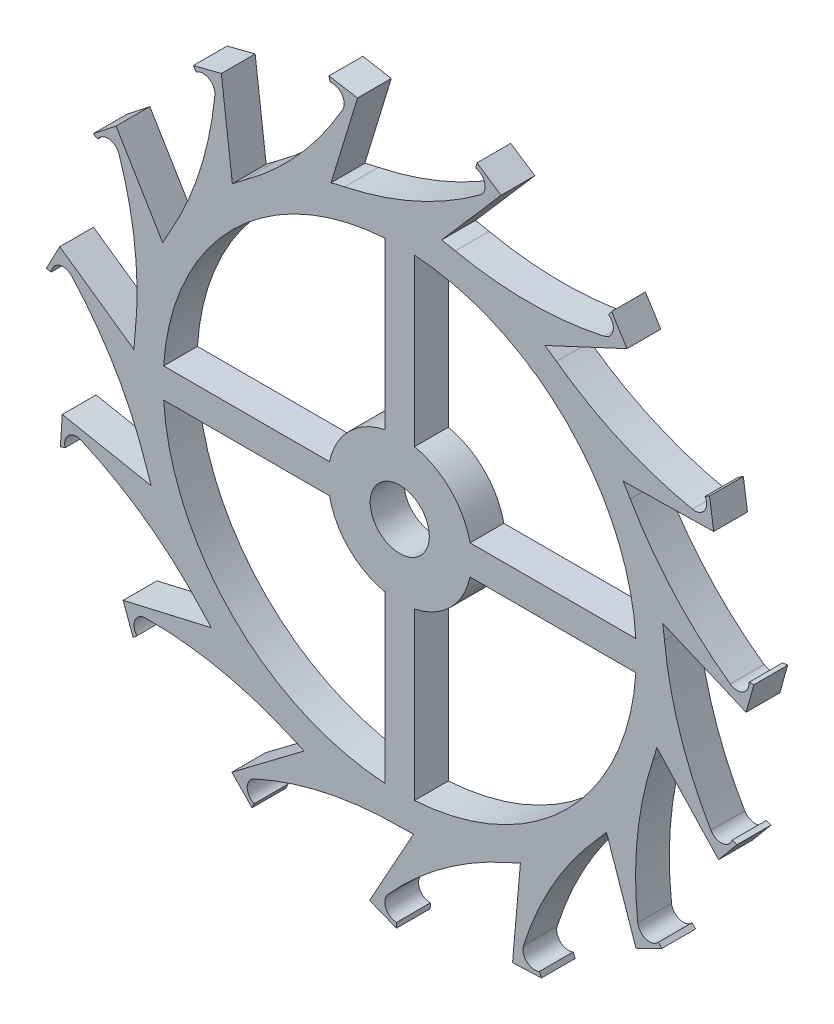
SolidWorks part; units mm, degrees
material "Brass"
ref_plane "Front Plane" through (0, 0, 0) normal (0, 0, 1) x (1, 0, 0)
ref_plane "Top Plane" through (0, 0, 0) normal (0, 1, 0) x (1, 0, 0)
ref_plane "Right Plane" through (0, 0, 0) normal (1, 0, 0) x (0, 0, -1)
sketch "Sketch1" plane through (0, 0, 0) normal (0, 0, 1) x (1, 0, 0)
  line L0 (0, -21.2809) -> (0, 20.8576) construction
  line L1 (-23.4901, 0) -> (24.9244, 0) construction
  line L2 (0, 0) -> (5.5969, 9.6942) construction
  line L3 (0, 0) -> (-5.6466, 9.7801) construction
  line L4 (2.05, 3.5507) -> (-1.6508, 5.6874) construction
  line L5 (-2.05, 3.5507) -> (1.6508, 5.6874) construction
  line L6 (0.8318, 0.175) -> (2.7945, 0.175)
  line L7 (0.8318, -0.175) -> (2.7945, -0.175)
  line L8 (-0.175, 0.8318) -> (-0.175, 2.7945)
  line L9 (0.175, 0.8318) -> (0.175, 2.7945)
  line L10 (0.175, -0.8318) -> (0.175, -2.7945)
  line L11 (-0.175, -0.8318) -> (-0.175, -2.7945)
  line L12 (-0.8318, -0.175) -> (-2.7945, -0.175)
  line L13 (-0.8318, 0.175) -> (-2.7945, 0.175)
  line L14 (0, 0) -> (6.6911, 7.6973) construction
  line L15 (0, 0) -> (-6.6911, 7.6973) construction
  line L16 (0, 4.7343) -> (6.5895, 2.1386) construction
  line L17 (2.6898, 3.0943) -> (2.2024, 3.8667)
  line L18 (0, 0) -> (2.5071, 3.384) construction
  line L19 (2.5071, 3.384) -> (2.4713, 3.3358)
  line L20 (2.6898, 3.0943) -> (1.7172, 2.6408)
  line L21 (3.6667, 2.0717) -> (3.6145, 2.0422)
  line L22 (3.7159, 1.7327) -> (3.5847, 2.6366)
  line L23 (3.7159, 1.7327) -> (2.6429, 1.714)
  line L24 (4.1923, 0.4012) -> (4.1326, 0.3955)
  line L25 (4.0994, 0.0716) -> (4.3472, 0.9506)
  line L26 (4.0994, 0.0716) -> (3.1115, 0.4909)
  line L27 (3.9931, -1.3387) -> (3.9362, -1.3196)
  line L28 (3.7741, -1.602) -> (4.3581, -0.8998)
  line L29 (3.7741, -1.602) -> (3.0422, -0.8171)
  line L30 (3.1034, -2.847) -> (3.0592, -2.8065)
  line L31 (2.7962, -2.9986) -> (3.6153, -2.5945)
  line L32 (2.7962, -2.9986) -> (2.4468, -1.9838)
  line L33 (1.6771, -3.8632) -> (1.6532, -3.8081)
  line L34 (1.3348, -3.8766) -> (2.2475, -3.8407)
  line L35 (1.3348, -3.8766) -> (1.4284, -2.8075)
  line L36 (-0.0392, -4.2113) -> (-0.0387, -4.1513)
  line L37 (-0.3573, -4.0844) -> (0.491, -4.4228)
  line L38 (-0.3573, -4.0844) -> (0.1629, -3.1458)
  line L39 (-1.7487, -3.8313) -> (-1.7238, -3.7767)
  line L40 (-1.9877, -3.5859) -> (-1.3504, -4.2401)
  line L41 (-1.9877, -3.5859) -> (-1.1306, -2.9401)
  line L42 (-3.1558, -2.7888) -> (-3.1109, -2.749)
  line L43 (-3.2744, -2.4674) -> (-2.9582, -3.3243)
  line L44 (-3.2744, -2.4674) -> (-2.2287, -2.226)
  line L45 (-4.0173, -1.2641) -> (-3.9601, -1.2461)
  line L46 (-3.9949, -0.9223) -> (-4.0546, -1.8337)
  line L47 (-3.9949, -0.9223) -> (-2.9415, -1.1271)
  line L48 (-4.1841, 0.4792) -> (-4.1245, 0.4724)
  line L49 (-4.0247, 0.7823) -> (-4.4499, -0.026)
  line L50 (-4.0247, 0.7823) -> (-3.1456, 0.1668)
  line L51 (-3.6275, 2.1396) -> (-3.5758, 2.1091)
  line L52 (-3.3585, 2.3517) -> (-4.0757, 1.7862)
  line L53 (-3.3585, 2.3517) -> (-2.8058, 1.4318)
  line L54 (-2.4436, 3.4301) -> (-2.4088, 3.3812)
  line L55 (-2.1117, 3.5144) -> (-2.9969, 3.2895)
  line L56 (-2.1117, 3.5144) -> (-1.9809, 2.4492)
  line L57 (-0.8372, 4.1274) -> (-0.8253, 4.0686)
  line L58 (-0.4997, 4.0694) -> (-0.8372, 4.1274)
  line L59 (-0.4997, 4.0694) -> (-0.8134, 3.0432)
  line L60 (0.9139, 4.1111) -> (0.9009, 4.0525)
  line L61 (1.1987, 3.9208) -> (0.9139, 4.1111)
  line L62 (1.1987, 3.9208) -> (0.4947, 3.1109)
  circle A1 centre (0, 4.7343) radius 0.25
  circle A2 centre (0, 0) radius 0.35
  arc A3 (-0.175, 0.8318) -> (-0.8318, 0.175) centre (0, 0) ccw
  arc A4 (-0.175, 2.7945) -> (-2.7945, 0.175) centre (0, 0) ccw
  arc A5 (0.6577, 3.0806) -> (0.4947, 3.1109) centre (0, 0) ccw
  arc A6 (-0.8318, -0.175) -> (-0.175, -0.8318) centre (0, 0) ccw
  arc A7 (0.8318, 0.175) -> (0.175, 0.8318) centre (0, 0) ccw
  arc A8 (0.175, -0.8318) -> (0.8318, -0.175) centre (0, 0) ccw
  arc A9 (-2.7945, -0.175) -> (-0.175, -2.7945) centre (0, 0) ccw
  arc A10 (2.7945, 0.175) -> (0.175, 2.7945) centre (0, 0) ccw
  arc A11 (0.175, -2.7945) -> (2.7945, -0.175) centre (0, 0) ccw
  arc A12 (2.05, 3.5507) -> (1.8799, 6.1728) centre (0, 4.7343) ccw
  arc A14 (2.4713, 3.3358) -> (2.4182, 3.0865) centre (2.388, 3.2233) cw
  arc A15 (0.6577, 3.0806) -> (2.4182, 3.0865) centre (1.5242, 7.1391) ccw
  arc A16 (1.8538, 2.5467) -> (3.4645, 1.8361) centre (4.2961, 5.902) ccw
  arc A17 (2.7628, 3.1783) -> (2.7631, 3.1784) centre (1.5242, 7.1391) ccw
  arc A18 (3.6145, 2.0422) -> (3.4645, 1.8361) centre (3.4926, 1.9733) cw
  arc A19 (2.7294, 1.5725) -> (3.9118, 0.2683) centre (6.3253, 3.6443) ccw
  arc A20 (4.1326, 0.3955) -> (3.9118, 0.2683) centre (3.9932, 0.3821) cw
  arc A21 (3.133, 0.3264) -> (3.6827, -1.346) centre (7.2607, 0.7565) ccw
  arc A22 (3.9362, -1.3196) -> (3.6827, -1.346) centre (3.8034, -1.2751) cw
  arc A23 (2.995, -0.9761) -> (2.8169, -2.7275) centre (6.9407, -2.2621) ccw
  arc A24 (3.0592, -2.8065) -> (2.8169, -2.7275) centre (2.956, -2.7118) cw
  arc A25 (2.339, -2.1099) -> (1.4639, -3.6375) centre (5.4206, -4.8895) ccw
  arc A26 (1.6532, -3.8081) -> (1.4639, -3.6375) centre (1.5974, -3.6797) cw
  arc A27 (1.2786, -2.8788) -> (-0.1421, -3.9184) centre (2.9632, -6.6715) ccw
  arc A28 (-0.0387, -4.1513) -> (-0.1421, -3.9184) centre (-0.0374, -4.0113) cw
  arc A29 (-0.0028, -3.15) -> (-1.7236, -3.5219) centre (-0.0066, -7.3) ccw
  arc A30 (-1.7238, -3.7767) -> (-1.7236, -3.5219) centre (-1.6657, -3.6493) cw
  arc A31 (-1.2838, -2.8765) -> (-3.007, -2.5163) centre (-2.9752, -6.6662) ccw
  arc A32 (-3.1109, -2.749) -> (-3.007, -2.5163) centre (-3.006, -2.6563) cw
  arc A33 (-2.3428, -2.1057) -> (-3.7706, -1.0757) centre (-5.4293, -4.8798) ccw
  arc A34 (-3.9601, -1.2461) -> (-3.7706, -1.0757) centre (-3.8265, -1.204) cw
  arc A35 (-2.9967, -0.9707) -> (-3.8821, 0.5509) centre (-6.9447, -2.2496) ccw
  arc A36 (-4.1245, 0.4724) -> (-3.8821, 0.5509) centre (-3.9854, 0.4564) cw
  arc A37 (-3.1324, 0.3321) -> (-3.3224, 2.0823) centre (-7.2593, 0.7696) ccw
  arc A38 (-3.5758, 2.1091) -> (-3.3224, 2.0823) centre (-3.4552, 2.038) cw
  arc A39 (-2.7266, 1.5775) -> (-2.1882, 3.2536) centre (-6.3187, 3.6557) ccw
  arc A40 (-2.4088, 3.3812) -> (-2.1882, 3.2536) centre (-2.3276, 3.2672) cw
  arc A41 (-1.8492, 2.5501) -> (-0.6757, 3.8623) centre (-4.2855, 5.9097) ccw
  arc A42 (-0.8253, 4.0686) -> (-0.6757, 3.8623) centre (-0.7975, 3.9314) cw
  arc A43 (-0.6522, 3.0818) -> (0.9537, 3.8033) centre (-1.5113, 7.1418) ccw
  arc A44 (0.9009, 4.0525) -> (0.9537, 3.8033) centre (0.8705, 3.9159) cw
  arc A45 (2.0666, 2.3773) -> (1.575, 2.728) centre (0, 0) ccw
  arc A46 (2.7294, 1.5725) -> (2.6429, 1.714) centre (0, 0) ccw
  arc A47 (3.133, 0.3264) -> (3.1115, 0.4909) centre (0, 0) ccw
  arc A48 (2.995, -0.9761) -> (3.0422, -0.8171) centre (0, 0) ccw
  arc A49 (2.339, -2.1099) -> (2.4468, -1.9838) centre (0, 0) ccw
  arc A50 (-0.6522, 3.0818) -> (-0.8134, 3.0432) centre (0, 0) ccw
  arc A51 (-1.575, 2.728) -> (-2.0666, 2.3773) centre (0, 0) ccw
  arc A52 (-2.7266, 1.5775) -> (-2.8058, 1.4318) centre (0, 0) ccw
  arc A53 (-3.1324, 0.3321) -> (-3.1456, 0.1668) centre (0, 0) ccw
  arc A54 (-2.9967, -0.9707) -> (-2.9415, -1.1271) centre (0, 0) ccw
  arc A55 (-2.3428, -2.1057) -> (-2.2287, -2.226) centre (0, 0) ccw
  arc A56 (-1.2838, -2.8765) -> (-1.1306, -2.9401) centre (0, 0) ccw
  arc A57 (-0.0028, -3.15) -> (0.1629, -3.1458) centre (0, 0) ccw
  arc A58 (1.2786, -2.8788) -> (1.4284, -2.8075) centre (0, 0) ccw
  point P36 (0, 0)
  point P40 (2.5071, 3.384)
  point P180 (0, 0)
  dimension "D4" = 0.5
  dimension "D5" = 0.7
  dimension "D6" = 1.7
  dimension "D7" = 5.6
  dimension "D8" = 6.3
  dimension "D17" = 0.14
  dimension "D18" = 8.3
  dimension "D2" = 60
  dimension "D3" = 30
  dimension "D9" = 0.35
  dimension "D11" = 11
  dimension "D12" = 8.5
  dimension "D13" = 0.9133
  dimension "D14" = 0.3425
  dimension "D15" = 0.06
  dimension "D16" = 24
  dimension "D10" = 4
  dimension "D19" = 15
extrude "Boss-Extrude1" add sketch "Sketch1" along normal blind 0.4
equation "\"D14@Sketch1\"=\"D13@Sketch1\"*3/8"
